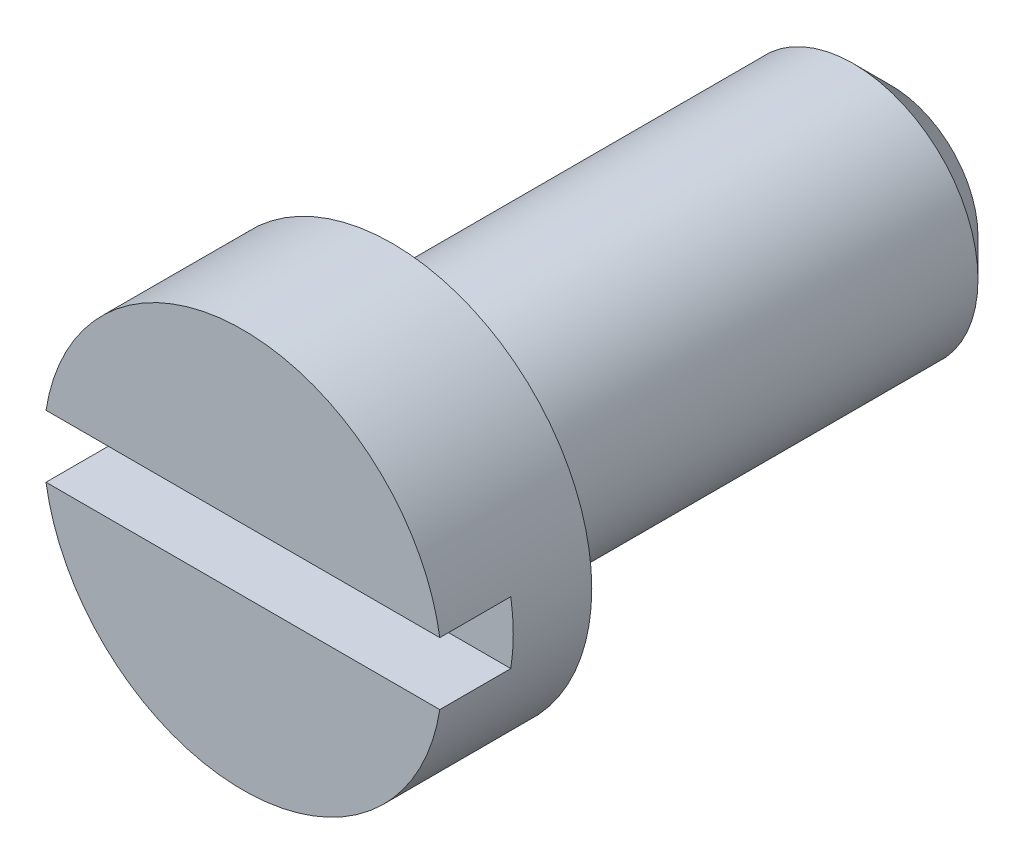
SolidWorks part; units mm, degrees
ref_plane "Спереди" through (0, 0, 0) normal (0, 0, 1) x (1, 0, 0)
ref_plane "Сверху" through (0, 0, 0) normal (0, 1, 0) x (1, 0, 0)
ref_plane "Справа" through (0, 0, 0) normal (1, 0, 0) x (0, 0, -1)
sketch "Эскиз12" plane through (0, 0, 0) normal (0, 0, 1) x (1, 0, 0)
  circle A0 centre (0, 0) radius 8
extrude "Вытянуть3" add sketch "Эскиз12" along normal blind 6
sketch "Эскиз13" plane through (0, 0, 0) normal (0, 0, -1) x (-1, 0, 0)
  circle A0 centre (0, 0) radius 5
extrude "Вытянуть4" add sketch "Эскиз13" along normal blind 20
sketch "Эскиз14" plane through (0, 0, 6) normal (0, 0, 1) x (1, 0, 0)
  line L0 (-8, 0) -> (8, 0) construction
  circle A0 centre (0, 0) radius 8 construction
sketch "Эскиз20" plane through (0, 0, 6) normal (0, 0, 1) x (1, 0, 0)
  line L0 (-8, 0) -> (8, 0) construction
  line L1 (-8.6822, 1.25) -> (8.5727, 1.25)
  line L2 (-8.6822, 1.25) -> (-8.6822, -1.25)
  line L3 (-8.6822, -1.25) -> (8.5727, -1.25)
  line L4 (8.5727, 1.25) -> (8.5727, -1.25)
  dimension "D1" = 1.25
  dimension "D2" = 1.25
extrude "Вырез-Вытянуть8" cut sketch "Эскиз20" against normal blind 2.85
chamfer "Фаска1" distance 1.5 angle 45 1 edges at (-5, 0, -20)
